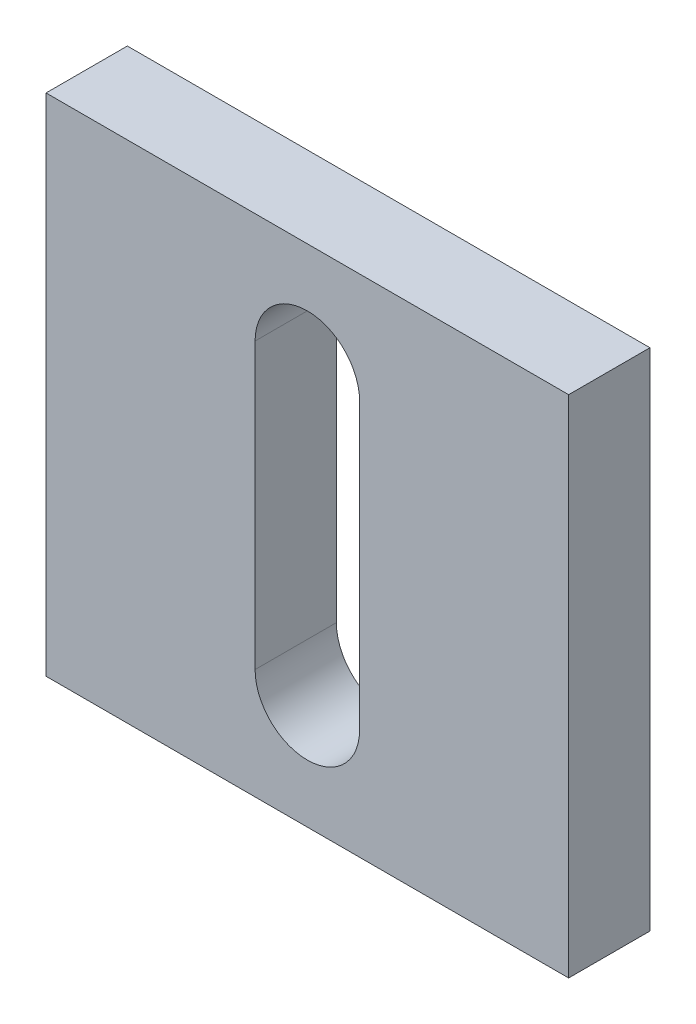
SolidWorks part; units mm, degrees
ref_plane "Front Plane" through (0, 0, 0) normal (0, 0, 1) x (1, 0, 0)
ref_plane "Top Plane" through (0, 0, 0) normal (0, 1, 0) x (1, 0, 0)
ref_plane "Right Plane" through (0, 0, 0) normal (1, 0, 0) x (0, 0, -1)
sketch "Sketch1" plane through (0, 0, 0) normal (0, 0, 1) x (1, 0, 0)
  line L0 (0, 0) -> (90, 0)
  line L1 (0, 0) -> (0, 87)
  line L2 (0, 87) -> (90, 87)
  line L3 (90, 87) -> (90, 0)
  dimension "D1" = 90
  dimension "D2" = 87
extrude "Boss-Extrude1" add sketch "Sketch1" along normal blind 14
sketch "Sketch2" plane through (0, 0, 14) normal (0, 0, 1) x (1, 0, 0)
  line L5 (0, 0) -> (90, 0) construction
  line L6 (54, 19) -> (54, 68)
  line L7 (36, 68) -> (36, 19)
  arc A0 (36, 19) -> (54, 19) centre (45, 19) ccw
  arc A1 (54, 68) -> (36, 68) centre (45, 68) ccw
  dimension "D3" = 18
  dimension "D5" = 18
  dimension "D1" = 45
  dimension "D2" = 19
  dimension "D4" = 49
extrude "Cut-Extrude1" cut sketch "Sketch2" against normal blind 63
